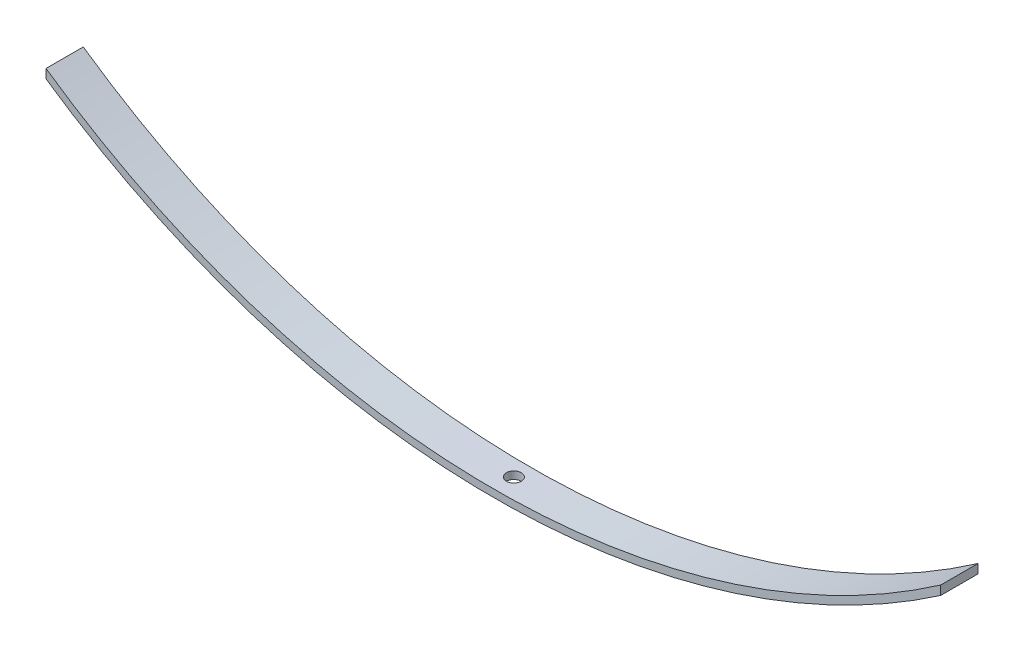
SolidWorks part; units mm, degrees
ref_plane "Front Plane" through (0, 0, 0) normal (0, 0, 1) x (1, 0, 0)
ref_plane "Top Plane" through (0, 0, 0) normal (0, 1, 0) x (1, 0, 0)
ref_plane "Right Plane" through (0, 0, 0) normal (1, 0, 0) x (0, 0, -1)
sketch "Sketch1" plane through (0, 0, 0) normal (0, 0, 1) x (1, 0, 0)
  line L0 (-600, -873.8421) -> (-600, -861.6844)
  line L1 (0, 0) -> (0, -3000.7365)
  line L2 (600, -873.8421) -> (600, -861.6844)
  arc A0 (-600, -873.8421) -> (600, -873.8421) centre (0, 0) ccw
  arc A1 (-600, -861.6844) -> (600, -861.6844) centre (0, 0) ccw
  point P7 (-600, -867.7632)
  dimension "D1" = 2120
  dimension "D2" = 2100
  dimension "D3" = 600
extrude "Boss-Extrude1" add sketch "Sketch1" along normal blind 50 contours A0 L2 A1 L0
sketch "Sketch3" plane through (0, 0, 0) normal (0, 1, 0) x (1, 0, 0)
  line L0 (0, 0) -> (0, -53.543) construction
  line L1 (600, 0) -> (-600, 0) construction
  circle A0 centre (0, -22.5) radius 10
  dimension "D1" = 20
  dimension "D2" = 22.5
extrude "Cut-Extrude1" cut sketch "Sketch3" against normal through all
